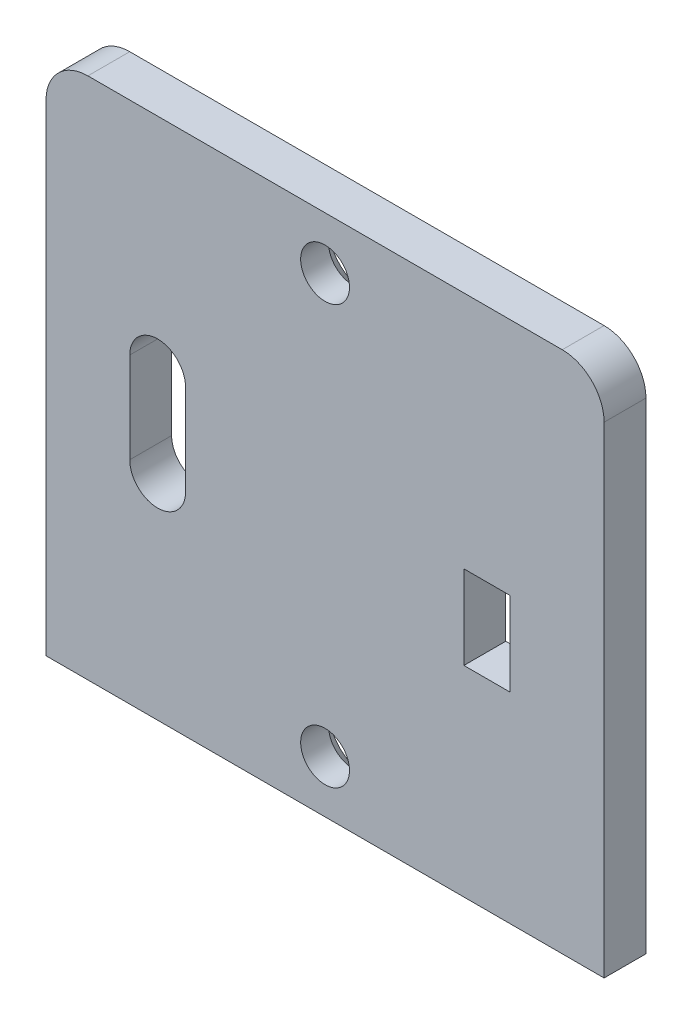
SolidWorks part; units mm, degrees
ref_plane "Plan de face" through (0, 0, 0) normal (0, 0, 1) x (1, 0, 0)
ref_plane "Plan de dessus" through (0, 0, 0) normal (0, 1, 0) x (1, 0, 0)
ref_plane "Plan de droite" through (0, 0, 0) normal (1, 0, 0) x (0, 0, -1)
sketch "Esquisse1" plane through (0, 0, 0) normal (0, 0, 1) x (1, 0, 0)
  line L0 (-10.7383, 27.2819) -> (-10.7383, -10.2181) construction
  line L1 (-30.7383, 27.2819) -> (9.2617, 27.2819)
  line L2 (-30.7383, 27.2819) -> (-30.7383, -10.2181)
  line L3 (-30.7383, -10.2181) -> (9.2617, -10.2181)
  line L4 (9.2617, 27.2819) -> (9.2617, -10.2181)
  line L5 (-30.7383, 27.2819) -> (9.2617, -10.2181) construction
  line L6 (-30.7383, -10.2181) -> (9.2617, 27.2819) construction
  circle A0 centre (-10.7383, -6.4681) radius 1.75
  circle A1 centre (-10.7383, 23.5319) radius 1.75
  point P0 (-10.7383, 8.5319)
  dimension "D3" = 3.5
  dimension "D4" = 3.5
  dimension "D5" = 3.75
  dimension "D6" = 3.75
  dimension "D1" = 40
  dimension "D2" = 37.5
extrude "Boss.-Extru.1" add sketch "Esquisse1" along normal blind 3
chamfer "Chanfrein1" distance 1 angle 45 2 edges at (-8.9883, -6.4681, 0) (-8.9883, 23.5319, 0)
fillet "Congé1" radius 3 2 edges at (9.2617, 27.2819, 1.5) (-30.7383, 27.2819, 1.5)
sketch "Esquisse5" plane through (0, 0, 0) normal (0, 0, -1) x (-1, 0, 0)
  line L0 (22.7383, 11.452) -> (22.7383, 4.952) construction
  line L4 (24.7383, 11.452) -> (24.7383, 4.952)
  line L5 (20.7383, 11.452) -> (20.7383, 4.952)
  line L6 (30.7383, 24.2819) -> (30.7383, -10.2181) construction
  line L7 (-2.5107, 10.1581) -> (0.7893, 10.1581)
  line L8 (-2.5107, 10.1581) -> (-2.5107, 4.1581)
  line L9 (-2.5107, 4.1581) -> (0.7893, 4.1581)
  line L10 (0.7893, 10.1581) -> (0.7893, 4.1581)
  arc A2 (24.7383, 11.452) -> (20.7383, 11.452) centre (22.7383, 11.452) ccw
  arc A3 (20.7383, 4.952) -> (24.7383, 4.952) centre (22.7383, 4.952) ccw
  point P2 (22.7383, 8.202)
  dimension "D1" = 2
  dimension "D2" = 6.5
  dimension "D3" = 6
  dimension "D4" = 3.3
  dimension "D5" = 6
extrude "Enlèv. mat.-Extru.2" cut sketch "Esquisse5" against normal through all
sketch "Esquisse6" plane through (0, 0, 0) normal (0, 0, -1) x (-1, 0, 0)
  line L0 (-0.8607, 10.1581) -> (-0.8607, 13.3985) construction
  line L1 (-2.5107, 10.1581) -> (0.7893, 10.1581)
  line L2 (-2.5107, 10.1581) -> (-2.5107, 4.1581)
  line L3 (-2.5107, 4.1581) -> (0.7893, 4.1581)
  line L4 (0.7893, 10.1581) -> (0.7893, 4.1581)
  line L5 (-0.8607, 4.1581) -> (-0.8607, -2.2043) construction
  circle A0 centre (-0.8607, 15.1581) radius 1
  circle A1 centre (-0.8607, -0.8419) radius 1
  dimension "D1" = 2
  dimension "D3" = 2
  dimension "D4" = 5
  dimension "D2" = 5
extrude "Boss.-Extru.2" add sketch "Esquisse6" along normal blind 2 contours A1 | A0
